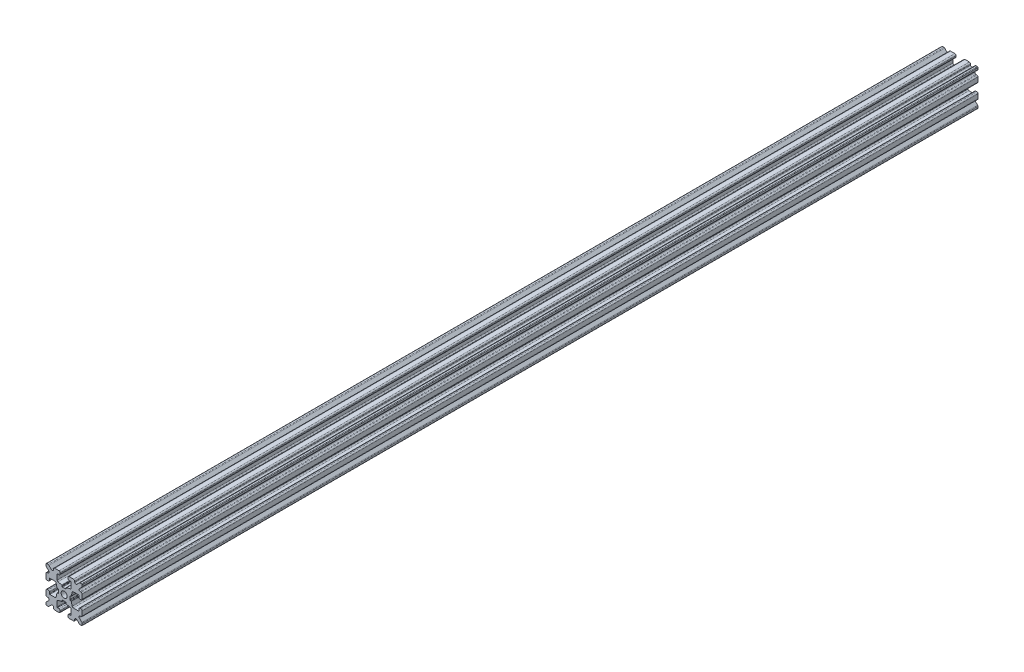
SolidWorks part; units mm, degrees
material "1060 Alloy"
ref_plane "Front Plane" through (0, 0, 0) normal (0, 0, 1) x (1, 0, 0)
ref_plane "Top Plane" through (0, 0, 0) normal (0, 1, 0) x (1, 0, 0)
ref_plane "Right Plane" through (0, 0, 0) normal (1, 0, 0) x (0, 0, -1)
sketch "Sketch1" plane through (0, 0, 0) normal (0, 0, 1) x (1, 0, 0)
  line L1 (-7.5, -7.5) -> (7.5, -7.5)
  line L2 (-7.5, -7.5) -> (-7.5, 7.5)
  line L3 (-7.5, 7.5) -> (7.5, 7.5)
  line L4 (7.5, -7.5) -> (7.5, 7.5)
  line L5 (-7.5, -7.5) -> (7.5, 7.5) construction
  line L6 (-7.5, 7.5) -> (7.5, -7.5) construction
  circle A0 centre (0, 0) radius 1.25
  point P0 (0, 0)
  dimension "D2" = 2.5
  dimension "D1" = 15
extrude "Boss-Extrude1" add sketch "Sketch1" along normal mid plane 371
fillet "Fillet1" radius 0.25 4 edges at (7.5, -7.5, 0) (-7.5, -7.5, 0) (7.5, 7.5, 0) (-7.5, 7.5, 0)
sketch "Sketch2" plane through (0, 0, 185.5) normal (0, 0, 1) x (1, 0, 0)
  line L0 (-7.5, 7.25) -> (-7.5, -7.25) construction
  line L1 (-7.5, 1.6) -> (-6.1, 1.6)
  line L2 (-7.5, 1.6) -> (-7.5, -1.6)
  line L3 (-7.5, -1.6) -> (-6.1, -1.6)
  line L4 (-6.1, 1.6) -> (-6.1, 2.9)
  line L5 (0, 0) -> (-12.1036, 0) construction
  line L6 (-6.1, -2.9) -> (-3.4, -2.9)
  line L7 (0, 0) -> (-7.25, 7.25) construction
  line L8 (-6.1, 2.9) -> (-3.4, 2.9)
  line L9 (-3.4, -2.9) -> (-3.4, 2.9)
  line L10 (55, 0) -> (-55, 0) construction
  line L11 (-6.1, -2.9) -> (-6.1, -1.6)
  line L12 (2.9, 6.1) -> (1.6, 6.1)
  line L13 (2.9, 3.4) -> (-2.9, 3.4)
  line L14 (-2.9, 6.1) -> (-2.9, 3.4)
  line L15 (2.9, 6.1) -> (2.9, 3.4)
  line L16 (-1.6, 6.1) -> (-2.9, 6.1)
  line L17 (1.6, 7.5) -> (1.6, 6.1)
  line L18 (-1.6, 7.5) -> (1.6, 7.5)
  line L19 (-1.6, 7.5) -> (-1.6, 6.1)
  line L20 (-1.6, -7.5) -> (-1.6, -6.1)
  line L21 (-1.6, -7.5) -> (1.6, -7.5)
  line L22 (1.6, -7.5) -> (1.6, -6.1)
  line L23 (-1.6, -6.1) -> (-2.9, -6.1)
  line L24 (2.9, -6.1) -> (2.9, -3.4)
  line L25 (-2.9, -6.1) -> (-2.9, -3.4)
  line L26 (2.9, -3.4) -> (-2.9, -3.4)
  line L27 (2.9, -6.1) -> (1.6, -6.1)
  line L28 (6.1, -2.9) -> (6.1, -1.6)
  line L29 (3.4, -2.9) -> (3.4, 2.9)
  line L30 (6.1, 2.9) -> (3.4, 2.9)
  line L31 (6.1, -2.9) -> (3.4, -2.9)
  line L32 (6.1, 1.6) -> (6.1, 2.9)
  line L33 (7.5, -1.6) -> (6.1, -1.6)
  line L34 (7.5, 1.6) -> (7.5, -1.6)
  line L35 (7.5, 1.6) -> (6.1, 1.6)
  dimension "D1" = 3.2
  dimension "D2" = 5.8
  dimension "D3" = 1.4
  dimension "D4" = 2.7
extrude "Cut-Extrude1" cut sketch "Sketch2" against normal through all
sketch "Sketch4" plane through (0, 0, 185.5) normal (0, 0, 1) x (1, 0, 0)
  line L0 (-3.4, 2.9) -> (-2.75, 0)
  line L1 (55, 0) -> (-55, 0) construction
  line L2 (-2.75, 0) -> (-3.4, -2.9)
  line L3 (-3.4, -2.9) -> (-3.4, 2.9) construction
  line L4 (-3.4, 2.9) -> (-3.4, -2.9)
  line L5 (-2.9, 3.4) -> (0, 2.75)
  line L6 (0, 2.75) -> (2.9, 3.4)
  line L7 (2.9, 3.4) -> (-2.9, 3.4)
  line L8 (3.4, 2.9) -> (2.75, 0)
  line L9 (2.75, 0) -> (3.4, -2.9)
  line L10 (3.4, -2.9) -> (3.4, 2.9)
  line L11 (-2.9, -3.4) -> (0, -2.75)
  line L12 (0, -2.75) -> (2.9, -3.4)
  line L13 (2.9, -3.4) -> (-2.9, -3.4)
  circle A2 centre (0, 0) radius 2.75
  circle A3 centre (0, 0) radius 2.75 construction
  dimension "D1" = 1.5
extrude "Cut-Extrude3" cut sketch "Sketch4" against normal through all
fillet "Fillet3" radius 0.5 16 edges at (-6.1, -1.6, 0) (-7.5, -1.6, 0) (-6.1, 1.6, 0) (-7.5, 1.6, 0) (-1.6, -7.5, 0) (-1.6, -6.1, 0) (1.6, -7.5, 0) (1.6, -6.1, 0) (6.1, -1.6, 0) (7.5, -1.6, 0) (7.5, 1.6, 0) (6.1, 1.6, 0) (1.6, 7.5, 0) (1.6, 6.1, 0) (-1.6, 7.5, 0) (-1.6, 6.1, 0)
fillet "Fillet4" radius 0.5 8 edges at (-3.4, 2.9, 0) (-3.4, -2.9, 0) (2.9, -3.4, 0) (-2.9, -3.4, 0) (3.4, -2.9, 0) (3.4, 2.9, 0) (-2.9, 3.4, 0) (2.9, 3.4, 0)
fillet "Fillet5" radius 3 4 edges at (0, -2.75, 0) (2.75, 0, 0) (-2.75, 0, 0) (0, 2.75, 0)
fillet "Fillet6" radius 0.2 8 edges at (-2.9, -6.1, 0) (2.9, -6.1, 0) (6.1, -2.9, 0) (6.1, 2.9, 0) (2.9, 6.1, 0) (-2.9, 6.1, 0) (-6.1, -2.9, 0) (-6.1, 2.9, 0)
sketch "Sketch5" plane through (0, 0, 185.5) normal (0, 0, 1) x (1, 0, 0)
  line L0 (0, 0) -> (-7.25, 7.25) construction
  line L1 (-7.5, 6.4393) -> (-5.4607, 4.4)
  line L2 (-6.4393, 7.5) -> (-4.4, 5.4607)
  line L3 (-7.5, 4.4) -> (-5.4607, 4.4)
  line L4 (-3.8003, 2.9) -> (-5.9, 2.9) construction
  line L5 (0, 0) -> (-12.1819, 0) construction
  line L6 (-4.4, 7.5) -> (-4.4, 5.4607)
  line L7 (-2.9, 5.9) -> (-2.9, 3.8003) construction
  line L8 (-7.5, 6.4393) -> (-7.5, 4.4)
  line L9 (-7.5, 7.25) -> (-7.5, 2.1) construction
  line L10 (2.1, -7.5) -> (7.25, -7.5) construction
  line L11 (7.5, -7.25) -> (7.5, -2.1) construction
  line L12 (7.25, 7.5) -> (2.1, 7.5) construction
  line L13 (-2.1, 7.5) -> (-7.25, 7.5) construction
  line L14 (-4.4, 7.5) -> (-6.4393, 7.5)
  line L16 (55, 0) -> (-55, 0) construction
  line L17 (0, 0) -> (0, 10.993) construction
  line L18 (0, -54.6431) -> (0, 54.6431) construction
  line L20 (4.4, 7.5) -> (6.4393, 7.5)
  line L22 (7.5, 6.4393) -> (7.5, 4.4)
  line L23 (4.4, 7.5) -> (4.4, 5.4607)
  line L24 (7.5, 4.4) -> (5.4607, 4.4)
  line L25 (6.4393, 7.5) -> (4.4, 5.4607)
  line L26 (7.5, 6.4393) -> (5.4607, 4.4)
  line L27 (7.5, -6.4393) -> (5.4607, -4.4)
  line L28 (6.4393, -7.5) -> (4.4, -5.4607)
  line L29 (7.5, -4.4) -> (5.4607, -4.4)
  line L30 (4.4, -7.5) -> (4.4, -5.4607)
  line L31 (7.5, -6.4393) -> (7.5, -4.4)
  line L33 (4.4, -7.5) -> (6.4393, -7.5)
  line L36 (-4.4, -7.5) -> (-6.4393, -7.5)
  line L38 (-7.5, -6.4393) -> (-7.5, -4.4)
  line L39 (-4.4, -7.5) -> (-4.4, -5.4607)
  line L40 (-7.5, -4.4) -> (-5.4607, -4.4)
  line L41 (-6.4393, -7.5) -> (-4.4, -5.4607)
  line L42 (-7.5, -6.4393) -> (-5.4607, -4.4)
  dimension "D1" = 1.5
  dimension "D2" = 1.5
  dimension "D3" = 1.5
extrude "Cut-Extrude4" cut sketch "Sketch5" against normal through all
fillet "Fillet8" radius 0.5 24 edges at (-5.4607, 4.4, 0) (-7.5, 4.4, 0) (-5.4607, -4.4, 0) (-7.5, -4.4, 0) (-4.4, -7.5, 0) (-4.4, -5.4607, 0) (4.4, -7.5, 0) (4.4, -5.4607, 0) (5.4607, -4.4, 0) (7.5, -4.4, 0) (7.5, 4.4, 0) (5.4607, 4.4, 0) (4.4, 5.4607, 0) (4.4, 7.5, 0) (-4.4, 5.4607, 0) (-4.4, 7.5, 0) (-6.4393, 7.5, 0) (-7.5, 6.4393, 0) (6.4393, 7.5, 0) (7.5, 6.4393, 0) (6.4393, -7.5, 0) (7.5, -6.4393, 0) (-6.4393, -7.5, 0) (-7.5, -6.4393, 0)
sketch "Sketch6" plane through (0, 0, 185.5) normal (0, 0, 1) x (1, 0, 0)
  line L0 (0, 0) -> (0, 11.013) construction
  line L1 (0.6561, 2.8971) -> (2.1235, 2.8971) construction
  line L2 (0, -54.6431) -> (0, 54.6431) construction
  line L3 (0, 0) -> (7.25, 7.25) construction
  line L4 (7.5, 0.8255) -> (7.5, -0.8255)
  line L5 (2.3471, 0.8255) -> (7.5, 0.8255)
  line L6 (0, 0) -> (12.4016, 0) construction
  line L7 (0.8255, -7.5) -> (-0.8255, -7.5)
  line L8 (2.3471, -0.8255) -> (2.3471, 0.8255)
  line L9 (0.8255, -2.3471) -> (0.8255, -7.5)
  line L10 (7.5, -0.8255) -> (2.3471, -0.8255)
  line L11 (-7.5, -0.8255) -> (-2.3471, -0.8255)
  line L12 (-2.3471, -0.8255) -> (-2.3471, 0.8255)
  line L13 (-0.8255, -2.3471) -> (0.8255, -2.3471)
  line L14 (-0.8255, 7.5) -> (-0.8255, 2.3471)
  line L15 (-0.8255, 2.3471) -> (0.8255, 2.3471)
  line L16 (-0.8255, -7.5) -> (-0.8255, -2.3471)
  line L17 (0.8255, 2.3471) -> (0.8255, 7.5)
  line L18 (0.8255, 7.5) -> (-0.8255, 7.5)
  line L19 (3.9, 7.5) -> (2.1, 7.5) construction
  line L20 (-2.3471, 0.8255) -> (-7.5, 0.8255)
  line L21 (-7.5, 0.8255) -> (-7.5, -0.8255)
  point P5 (0, -2.5973)
  point P7 (0, 2.5973)
  dimension "D3" = 0.55
  dimension "D1" = 1.651
extrude "Cut-Extrude5" cut sketch "Sketch6" against normal through all
fillet "Fillet10" radius 0.2 16 edges at (-2.935, 0.8255, 0) (-2.935, -0.8255, 0) (2.935, -0.8255, 0) (2.935, 0.8255, 0) (0.8255, 2.935, 0) (-0.8255, 2.935, 0) (-2.3471, 0.8255, 0) (-2.3471, -0.8255, 0) (0.8255, 2.3471, 0) (-0.8255, 2.3471, 0) (2.3471, 0.8255, 0) (2.3471, -0.8255, 0) (0.8255, -2.935, 0) (0.8255, -2.3471, 0) (-0.8255, -2.3471, 0) (-0.8255, -2.935, 0)
